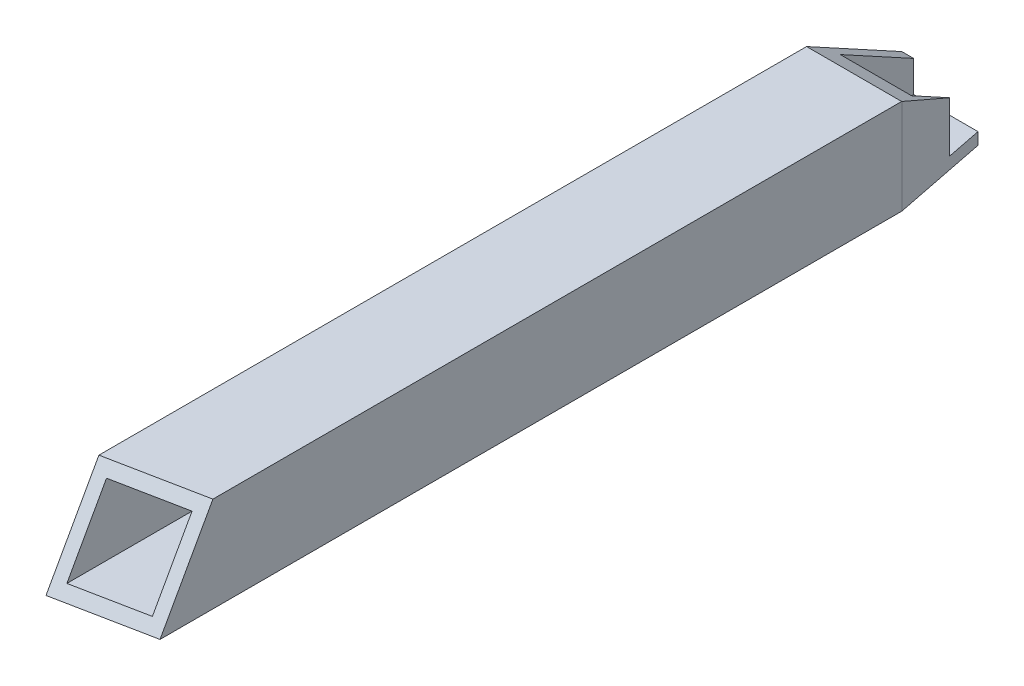
SolidWorks part; units mm, degrees
material "6061 Alloy"
ref_plane "Front Plane" through (0, 0, 0) normal (0, 0, 1) x (1, 0, 0)
ref_plane "Top Plane" through (0, 0, 0) normal (0, 1, 0) x (1, 0, 0)
ref_plane "Right Plane" through (0, 0, 0) normal (1, 0, 0) x (0, 0, -1)
sketch "Sketch1" plane through (0, 0, 0) normal (0, 0, 1) x (1, 0, 0)
  line L0 (12.7, 0) -> (9.525, 0) construction
  line L1 (-12.7, 0) -> (12.7, 0) construction
  line L2 (0, 12.7) -> (0, -12.7)
  point P7 (0, 0)
sketch "Sketch2" plane through (0, 0, 0) normal (1, 0, 0) x (0, 0, -1)
  line L0 (114.3, 0) -> (-114.3, 0)
  point P4 (0, 0)
  dimension "Length" = 228.6
sketch "Sketch3" plane through (0, 0, 0) normal (0, 0, 1) x (1, 0, 0)
  line L0 (-12.7, 0) -> (12.7, 0) construction
  line L5 (12.7, -12.7) -> (-12.7, -12.7)
  line L6 (12.7, -12.7) -> (12.7, 12.7)
  line L11 (12.7, 12.7) -> (-12.7, 12.7)
  line L12 (-12.7, -12.7) -> (-12.7, 12.7)
  line L14 (12.7, -12.7) -> (-12.7, 12.7) construction
  line L15 (12.7, 12.7) -> (-12.7, -12.7) construction
  line L16 (9.525, -9.525) -> (-9.525, -9.525)
  line L17 (9.525, -9.525) -> (9.525, 9.525)
  line L18 (9.525, 9.525) -> (-9.525, 9.525)
  line L19 (-9.525, -9.525) -> (-9.525, 9.525)
  line L20 (9.525, -9.525) -> (-9.525, 9.525) construction
  line L21 (9.525, 9.525) -> (-9.525, -9.525) construction
  point P0 (0, 0)
  point P5 (0, 0)
  point P13 (9.525, -12.7)
  dimension "D1" = 3.175
  dimension "D3" = 25.4
  dimension "D4" = 25.4
extrude "Boss-Extrude1" add sketch "Sketch3" along normal up to vertex (114.3 mm away) and the other way up to vertex (114.3 mm away) up to point (0, 0, 114.3) other way up to point (0, 0, -114.3)
sketch "Sketch5" plane through (0, 0, 0) normal (1, 0, 0) x (0, 0, -1)
  line L0 (-114.3, 0) -> (114.3, 0) construction
  line L3 (-114.3, -12.7) -> (-114.3, 12.7) construction
  line L4 (114.3, -12.7) -> (114.3, 12.7) construction
  point P6 (-85.725, 0)
  point P7 (-76.2, 0)
  point P8 (76.2, 0)
  point P10 (85.725, 0)
  dimension "D1" = 28.575
  dimension "D2" = 38.1
  dimension "D3" = 28.575
  dimension "D4" = 38.1
sketch "Sketch7" plane through (0, -12.7, 0) normal (0, -1, 0) x (1, 0, 0)
  line L0 (-12.7, 114.3) -> (12.7, 109.243) construction
  line L1 (12.7, 114.3) -> (12.7, -114.3) construction
  line L2 (-12.7, 114.3) -> (12.7, 114.3) construction
  dimension "D1" = 11.26
ref_plane "Plane2" through (21.4046, 0, 107.51) normal (0.1953, 0, 0.9808) x (0, -1, 0)
ref_plane "Plane3" through (15.4542, 43.1698, 77.6227) normal (0.1714, 0.4788, 0.861) x (0.9808, 0, -0.1953)
other "SurfaceCut2"
sketch "Sketch8" plane through (0, -12.7, 0) normal (0, -1, 0) x (1, 0, 0)
  line L0 (12.7, -88.9) -> (7.643, -114.3) construction
  line L1 (12.7, 109.243) -> (12.7, -114.3) construction
  line L2 (-12.7, -114.3) -> (12.7, -114.3) construction
  dimension "D1" = 11.26
  dimension "D2" = 25.4
sketch "Sketch11" plane through (-12.7, 0, 0) normal (-1, 0, 0) x (0, 0, 1)
  line L0 (-114.3, -1.1888) -> (-88.9, 12.7) construction
  line L1 (-114.3, 12.7) -> (-114.3, -12.7) construction
  line L2 (100.0375, 12.7) -> (-114.3, 12.7) construction
  dimension "D1" = 28.67
  dimension "D2" = 25.4
sketch "Sketch9" plane through (0, 0, -114.3) normal (0, 0, -1) x (-1, 0, 0)
  line L0 (-7.643, -12.7) -> (-7.643, 12.7) construction
  line L1 (-12.7, 12.7) -> (12.7, 12.7) construction
  line L2 (12.7, -1.1793) -> (-12.7, -1.1793) construction
  line L3 (12.7, 12.7) -> (12.7, -12.7) construction
  line L4 (-12.7, -12.7) -> (-12.7, 12.7) construction
ref_plane "Plane4" through (29.2404, 0, -5.8216) normal (0.9808, 0, -0.1953) x (0, 1, 0)
other "SurfaceCut4"
ref_plane "Plane6" through (0, 47.1403, -25.7124) normal (0, 0.8779, -0.4788) x (1, 0, 0)
other "SurfaceCut5"
equation "\"D1@Sketch3\"=\"Wall thickness@Sketch1\""
equation "\"D1@Sketch5\"=\"Width@Sketch1\"*1.125"
equation "\"D2@Sketch5\"=\"Width@Sketch1\"*1.5"
equation "\"D3@Sketch5\"=\"D1@Sketch5\""
equation "\"D4@Sketch5\"=\"D2@Sketch5\""
equation "\"D2@Sketch3\"=\"Wall Thickness@Sketch1\""
